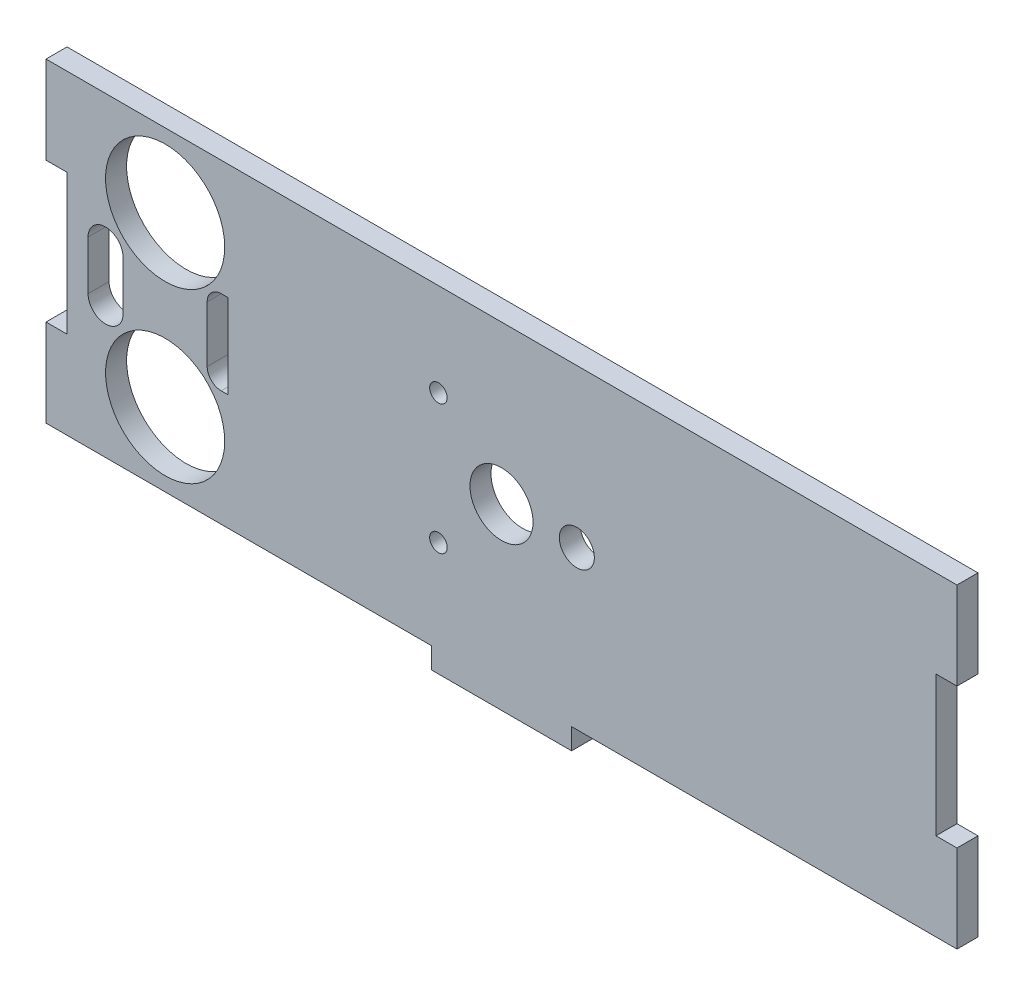
SolidWorks part; units mm, degrees
ref_plane "Front Plane" through (0, 0, 0) normal (0, 0, 1) x (1, 0, 0)
ref_plane "Top Plane" through (0, 0, 0) normal (0, 1, 0) x (1, 0, 0)
ref_plane "Right Plane" through (0, 0, 0) normal (1, 0, 0) x (0, 0, -1)
sketch "Sketch1" plane through (0, 0, 0) normal (0, 0, 1) x (1, 0, 0)
  line L0 (-10, -22.5) -> (-65, -22.5)
  line L1 (65, -22.5) -> (10, -22.5)
  line L2 (65, -22.5) -> (65, -10)
  line L3 (65, 22.5) -> (-65, 22.5)
  line L4 (-65, -22.5) -> (-65, -10)
  line L5 (65, -22.5) -> (-65, 22.5) construction
  line L6 (65, 22.5) -> (-65, -22.5) construction
  line L8 (-10, -22.5) -> (-10, -25.5)
  line L9 (-10, -25.5) -> (10, -25.5)
  line L10 (10, -22.5) -> (10, -25.5)
  line L11 (0, -55) -> (0, 55) construction
  line L12 (-62, -10) -> (-65, -10)
  line L13 (-62, -10) -> (-62, 10)
  line L14 (-62, 10) -> (-65, 10)
  line L16 (-62, -10) -> (-65, 10) construction
  line L17 (-62, 10) -> (-65, -10) construction
  line L18 (62, 10) -> (65, 10)
  line L20 (62, -10) -> (65, -10)
  line L21 (62, -10) -> (62, 10)
  line L22 (-65, 10) -> (-65, 22.5)
  line L23 (65, 10) -> (65, 22.5)
  line L24 (-56.5, 3.5) -> (-56.5, -3.5) construction
  line L29 (-54, 3.5) -> (-54, -3.5)
  line L30 (-59, 3.5) -> (-59, -3.5)
  line L31 (-39, -6) -> (-40, -6)
  line L32 (-39, -6) -> (-39, 6)
  line L33 (-39, 6) -> (-40, 6)
  line L34 (-42, -4) -> (-42, 4)
  line L35 (-39, -6) -> (-42, 6) construction
  line L36 (-39, 6) -> (-42, -6) construction
  line L37 (55, 0) -> (-55, 0) construction
  circle A0 centre (-48, 12) radius 8.5
  circle A1 centre (-48, -12) radius 8.5
  circle A6 centre (0, 0) radius 4.5
  circle A7 centre (10.75, 0) radius 2.5
  arc A10 (-54, 3.5) -> (-59, 3.5) centre (-56.5, 3.5) ccw
  arc A11 (-59, -3.5) -> (-54, -3.5) centre (-56.5, -3.5) ccw
  arc A12 (-40, -6) -> (-42, -4) centre (-40, -4) cw
  arc A13 (-40, 6) -> (-42, 4) centre (-40, 4) ccw
  circle A14 centre (-9, 9.25) radius 1.25
  circle A15 centre (-9, -9.25) radius 1.25
  point P0 (0, 0)
  point P10 (-63.5, 0)
  point P26 (-56.5, 0)
  point P49 (-40.5, 0)
  dimension "D8" = 17
  dimension "D15" = 2
  dimension "D16" = 9
  dimension "D17" = 5
  dimension "D22" = 2.5
  dimension "D12" = 2.5
  dimension "D1" = 130
  dimension "D2" = 45
  dimension "D3" = 3
  dimension "D4" = 20
  dimension "D5" = 55
  dimension "D6" = 20
  dimension "D7" = 3
  dimension "D9" = 17
  dimension "D10" = 24
  dimension "D11" = 12
  dimension "D13" = 7
  dimension "D14" = 6
  dimension "D18" = 10.75
  dimension "D19" = 3
  dimension "D20" = 12
  dimension "D21" = 6
  dimension "D23" = 9
  dimension "D24" = 9.25
extrude "Boss-Extrude1" add sketch "Sketch1" along normal blind 3
